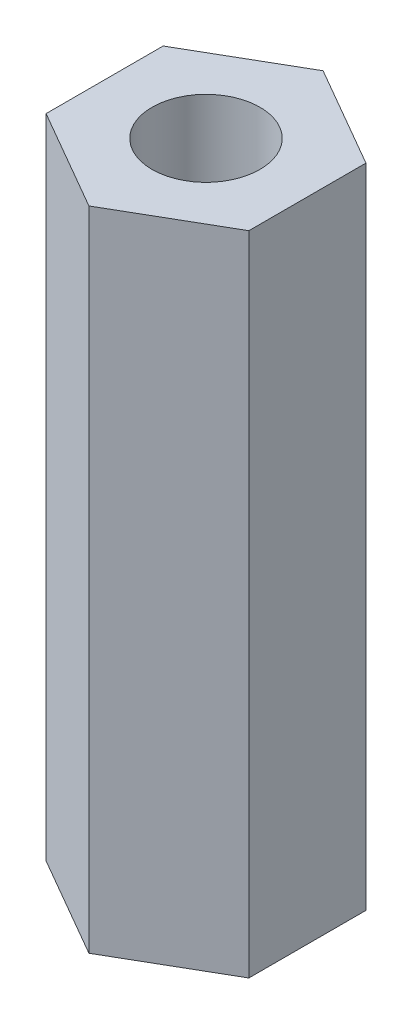
SolidWorks part; units mm, degrees
ref_plane "Front Plane" through (0, 0, 0) normal (0, 0, 1) x (1, 0, 0)
ref_plane "Top Plane" through (0, 0, 0) normal (0, 1, 0) x (1, 0, 0)
ref_plane "Right Plane" through (0, 0, 0) normal (1, 0, 0) x (0, 0, -1)
sketch "Sketch1" plane through (0, 0, 0) normal (0, 1, 0) x (1, 0, 0)
  circle A0 centre (0, 0) radius 1.5
  dimension "D1" = 3
extrude "Boss-Extrude1" add sketch "Sketch1" along normal blind 6
sketch "Sketch2" plane through (0, 6, 0) normal (0, 1, 0) x (1, 0, 0)
  line L1 (-2.35, 1.3568) -> (-2.35, -1.3568)
  line L2 (-2.35, -1.3568) -> (0, -2.7135)
  line L3 (0, -2.7135) -> (2.35, -1.3568)
  line L4 (2.35, -1.3568) -> (2.35, 1.3568)
  line L5 (2.35, 1.3568) -> (0, 2.7135)
  line L6 (0, 2.7135) -> (-2.35, 1.3568)
  circle A0 centre (0, 0) radius 2.35 construction
  dimension "D1" = 4.7
extrude "Boss-Extrude2" add sketch "Sketch2" along normal blind 15
sketch "Sketch3" plane through (0, 21, 0) normal (0, 1, 0) x (1, 0, 0)
  circle A0 centre (0, 0) radius 1.25
  dimension "D1" = 2.5
extrude "Cut-Extrude1" cut sketch "Sketch3" against normal through all
sketch "Sketch4" plane through (0, 6, 0) normal (0, -1, 0) x (1, 0, 0)
  circle A0 centre (0, 0) radius 1.754
extrude "Cut-Extrude2" cut sketch "Sketch4" along normal blind 10
